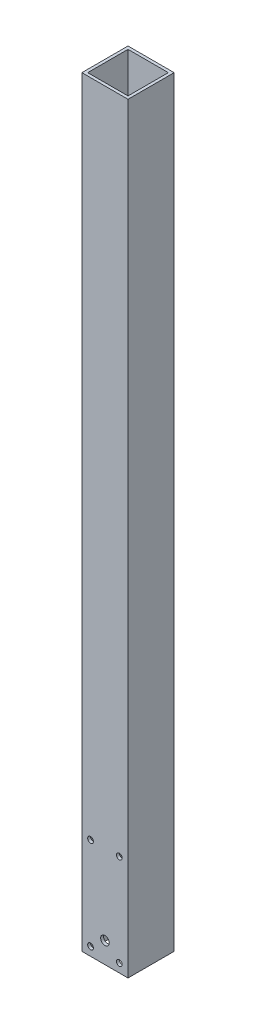
SolidWorks part; units mm, degrees
material "1060 Alloy"
ref_plane "Front Plane" through (0, 0, 0) normal (0, 0, 1) x (1, 0, 0)
ref_plane "Top Plane" through (0, 0, 0) normal (0, 1, 0) x (1, 0, 0)
ref_plane "Right Plane" through (0, 0, 0) normal (1, 0, 0) x (0, 0, -1)
sketch "Sketch1" plane through (0, 0, 0) normal (0, 1, 0) x (1, 0, 0)
  line L0 (3.175, 47.625) -> (47.625, 47.625)
  line L1 (0, 0) -> (50.8, 0)
  line L2 (0, 0) -> (0, 50.8)
  line L3 (0, 50.8) -> (50.8, 50.8)
  line L4 (50.8, 0) -> (50.8, 50.8)
  line L5 (47.625, 3.175) -> (47.625, 47.625)
  line L6 (3.175, 3.175) -> (47.625, 3.175)
  line L7 (3.175, 3.175) -> (3.175, 47.625)
  dimension "D1" = 50.8
  dimension "D2" = 3.175
extrude "Boss-Extrude1" add sketch "Sketch1" along normal blind 838.2
sketch "Sketch2" plane through (0, 0, 0) normal (0, 0, 1) x (1, 0, 0)
  line L0 (0, 838.2) -> (0, 0) construction
  line L1 (0, 0) -> (50.8, 0) construction
  line L2 (50.8, 838.2) -> (50.8, 0) construction
  circle A0 centre (9.525, 111.125) radius 3.175
  circle A1 centre (41.275, 111.125) radius 3.175
  circle A2 centre (9.525, 9.525) radius 3.175
  circle A3 centre (41.275, 9.525) radius 3.175
  circle A4 centre (25.4, 23.114) radius 4.7625
  point P13 (25.4, 0)
  dimension "D1" = 6.35
  dimension "D6" = 9.525
  dimension "D2" = 9.525
  dimension "D3" = 9.525
  dimension "D4" = 9.525
  dimension "D5" = 111.125
  dimension "D7" = 23.114
extrude "Cut-Extrude1" cut sketch "Sketch2" against normal through all
ref_plane "Plane1" [suppressed] through (0, 419.1, 0) normal (0, 1, 0) x (1, 0, 0)
mirror "Mirror1" [suppressed] about plane through (0, 419.1, 0) normal (0, 1, 0)
